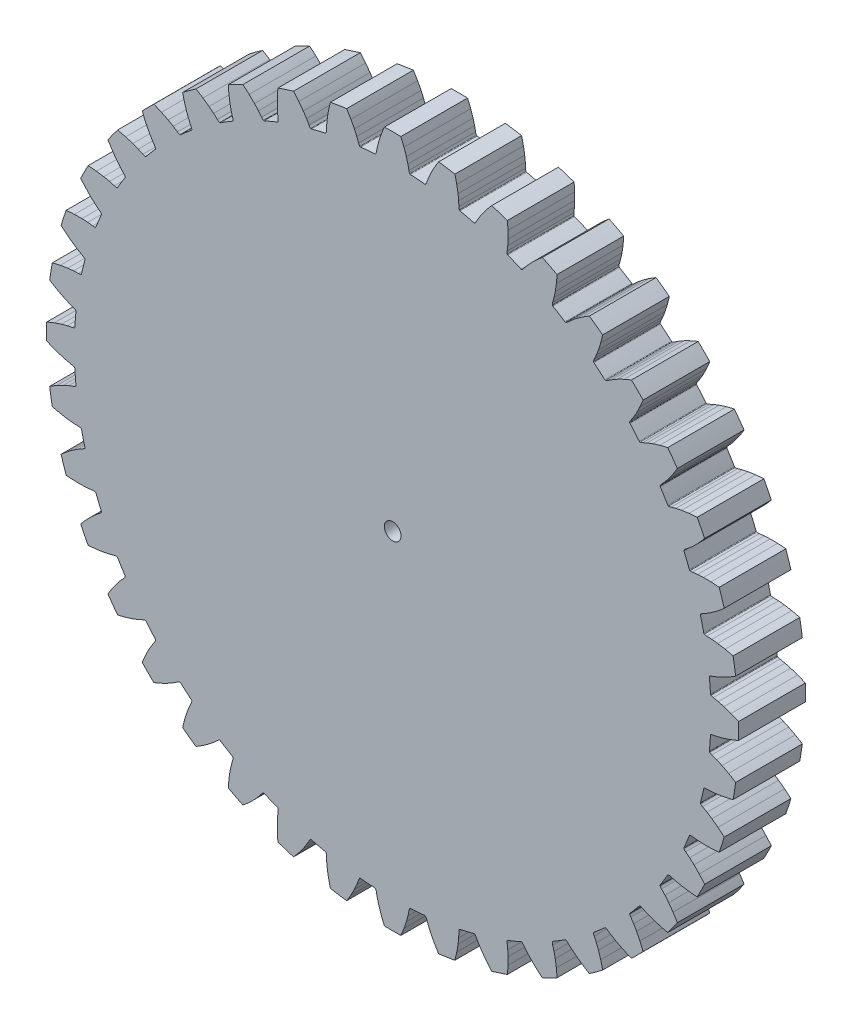
SolidWorks part; units mm, degrees
ref_plane "Front Plane" through (0, 0, 0) normal (0, 0, 1) x (1, 0, 0)
ref_plane "Top Plane" through (0, 0, 0) normal (0, 1, 0) x (1, 0, 0)
ref_plane "Right Plane" through (0, 0, 0) normal (1, 0, 0) x (0, 0, -1)
sketch "Model" plane through (0, 0, 0) normal (0, 0, 1) x (1, 0, 0)
  arc A1 (60.4326, -4.7561) -> (60.5251, -3.3796) centre (0, 0) ccw
  arc A2 (60.6099, -3.2458) -> (60.5251, -3.3796) centre (60.6875, -3.3887) ccw
  arc A3 (61.0557, -3.0916) -> (60.6099, -3.2458) centre (61.2975, -4.5122) ccw
  arc A4 (61.0557, -3.0916) -> (62.0044, -2.8977) centre (58.5908, 11.3846) ccw
  arc A5 (62.0044, -2.8977) -> (63.0847, -2.6067) centre (57.4472, 16.1693) ccw
  arc A6 (63.0847, -2.6067) -> (64.4306, -2.1546) centre (56.7644, 18.4435) ccw
  arc A7 (64.4306, -2.1546) -> (65.8858, -1.5642) centre (55.0531, 23.0418) ccw
  arc A8 (65.8858, -1.5642) -> (65.8858, 1.5642) centre (0, 0) ccw
  arc A9 (65.8858, 1.5642) -> (64.4306, 2.1546) centre (55.0531, -23.0418) ccw
  arc A10 (64.4306, 2.1546) -> (63.0847, 2.6067) centre (56.7644, -18.4435) ccw
  arc A11 (63.0847, 2.6067) -> (62.0044, 2.8977) centre (57.4472, -16.1693) ccw
  arc A12 (62.0044, 2.8977) -> (61.0557, 3.0916) centre (58.5908, -11.3846) ccw
  arc A13 (60.6099, 3.2458) -> (61.0557, 3.0916) centre (61.2975, 4.5122) ccw
  arc A14 (60.5251, 3.3796) -> (60.6099, 3.2458) centre (60.6875, 3.3887) ccw
  arc A15 (60.5251, 3.3796) -> (60.3087, 6.1302) centre (0, 0) ccw
  arc A16 (60.3715, 6.2757) -> (60.3087, 6.1302) centre (60.4705, 6.1466) ccw
  arc A17 (60.7876, 6.4977) -> (60.3715, 6.2757) centre (61.2487, 5.1324) ccw
  arc A18 (60.7876, 6.4977) -> (61.6943, 6.8376) centre (56.0885, 20.41) ccw
  arc A19 (61.6943, 6.8376) -> (62.7158, 7.294) centre (54.2105, 24.957) ccw
  arc A20 (62.7158, 7.294) -> (63.9745, 7.9511) centre (53.1804, 27.0964) ccw
  arc A21 (63.9745, 7.9511) -> (65.3193, 8.7619) centre (50.7708, 31.3703) ccw
  arc A22 (65.3193, 8.7619) -> (64.8299, 11.8517) centre (0, 0) ccw
  arc A23 (64.8299, 11.8517) -> (63.3003, 12.2073) centre (57.9798, -14.1459) ccw
  arc A24 (63.3003, 12.2073) -> (61.9002, 12.4432) centre (58.9508, -9.3365) ccw
  arc A25 (61.9002, 12.4432) -> (60.7877, 12.5616) centre (59.2694, -6.9835) ccw
  arc A26 (60.7877, 12.5616) -> (59.8203, 12.6047) centre (59.6504, -2.0788) ccw
  arc A27 (59.356, 12.6873) -> (59.8203, 12.6047) centre (59.837, 14.0457) ccw
  arc A28 (59.2513, 12.8063) -> (59.356, 12.6873) centre (59.4102, 12.8406) ccw
  arc A29 (59.2513, 12.8063) -> (58.6072, 15.4891) centre (0, 0) ccw
  arc A30 (58.6465, 15.6426) -> (58.6072, 15.4891) centre (58.7644, 15.5306) ccw
  arc A31 (59.0227, 15.9269) -> (58.6465, 15.6426) centre (59.6918, 14.6506) ccw
  arc A32 (59.0227, 15.9269) -> (59.8651, 16.4045) centre (52.2052, 28.9329) ccw
  arc A33 (59.8651, 16.4045) -> (60.8026, 17.0152) centre (49.639, 33.1301) ccw
  arc A34 (60.8026, 17.0152) -> (61.943, 17.861) centre (48.2868, 35.082) ccw
  arc A35 (61.943, 17.861) -> (63.1444, 18.8722) centre (45.2383, 38.9263) ccw
  arc A36 (63.1444, 18.8722) -> (62.1777, 21.8474) centre (0, 0) ccw
  arc A37 (62.1777, 21.8474) -> (60.6114, 21.9594) centre (59.4789, -4.9017) ccw
  arc A38 (60.6114, 21.9594) -> (59.1916, 21.9733) centre (59.6855, 0.0004) ccw
  arc A39 (59.1916, 21.9733) -> (58.0742, 21.9163) centre (59.6322, 2.3742) ccw
  arc A40 (58.0742, 21.9163) -> (57.112, 21.8075) centre (59.2412, 7.2782) ccw
  arc A41 (56.6405, 21.8164) -> (57.112, 21.8075) centre (56.9031, 23.2334) ccw
  arc A42 (56.5185, 21.9175) -> (56.6405, 21.8164) centre (56.6701, 21.9763) ccw
  arc A43 (56.5185, 21.9175) -> (55.4626, 24.4666) centre (0, 0) ccw
  arc A44 (55.4774, 24.6243) -> (55.4626, 24.4666) centre (55.6114, 24.5322) ccw
  arc A45 (55.8045, 24.9641) -> (55.4774, 24.6243) centre (56.665, 23.8081) ccw
  arc A46 (55.8045, 24.9641) -> (56.5618, 25.5675) centre (47.0363, 36.7434) ccw
  arc A47 (56.5618, 25.5675) -> (57.3922, 26.3173) centre (43.8451, 40.4875) ccw
  arc A48 (57.3922, 26.3173) -> (58.3863, 27.3311) centre (42.2043, 42.2038) ccw
  arc A49 (58.3863, 27.3311) -> (59.4147, 28.5178) centre (38.5919, 45.5239) ccw
  arc A50 (59.4147, 28.5178) -> (57.9945, 31.3052) centre (0, 0) ccw
  arc A51 (57.9945, 31.3052) -> (56.4299, 31.1707) centre (59.5134, 4.4632) ccw
  arc A52 (56.4299, 31.1707) -> (55.0254, 30.9624) centre (58.9507, 9.3372) ccw
  arc A53 (55.0254, 30.9624) -> (53.9308, 30.7312) centre (58.5266, 11.6735) ccw
  arc A54 (53.9308, 30.7312) -> (52.9974, 30.4733) centre (57.3733, 16.456) ccw
  arc A55 (52.5303, 30.4083) -> (52.9974, 30.4733) centre (52.568, 31.8489) ccw
  arc A56 (52.394, 30.4891) -> (52.5303, 30.4083) centre (52.5345, 30.5709) ccw
  arc A57 (52.394, 30.4891) -> (50.9524, 32.8416) centre (0, 0) ccw
  arc A58 (50.9423, 32.9997) -> (50.9524, 32.8416) centre (51.0891, 32.9297) ccw
  arc A59 (51.2123, 33.3865) -> (50.9423, 32.9997) centre (52.243, 32.3793) ccw
  arc A60 (51.2123, 33.3865) -> (51.8658, 34.101) centre (40.7093, 43.6491) ccw
  arc A61 (51.8658, 34.101) -> (52.5687, 34.9714) centre (36.9717, 46.8479) ccw
  arc A62 (52.5687, 34.9714) -> (53.392, 36.1282) centre (35.0826, 48.2864) ccw
  arc A63 (53.392, 36.1282) -> (54.2221, 37.4613) centre (30.9953, 51.0006) ccw
  arc A64 (54.2221, 37.4613) -> (52.3833, 39.9921) centre (0, 0) ccw
  arc A65 (52.3833, 39.9921) -> (50.859, 39.6145) centre (58.0825, 13.7182) ccw
  arc A66 (50.859, 39.6145) -> (49.5044, 39.1891) centre (56.7642, 18.4442) ccw
  arc A67 (49.5044, 39.1891) -> (48.4594, 38.7895) centre (55.9799, 20.6854) ccw
  arc A68 (48.4594, 38.7895) -> (47.5779, 38.3888) centre (54.0927, 25.2285) ccw
  arc A69 (47.1266, 38.2515) -> (47.5779, 38.3888) centre (46.9385, 39.6803) ccw
  arc A70 (46.9794, 38.31) -> (47.1266, 38.2515) centre (47.1054, 38.4128) ccw
  arc A71 (46.9794, 38.31) -> (45.1875, 40.408) centre (0, 0) ccw
  arc A72 (45.1528, 40.5626) -> (45.1875, 40.408) centre (45.3087, 40.5164) ccw
  arc A73 (45.359, 40.9868) -> (45.1528, 40.5626) centre (46.5345, 40.1533) ccw
  arc A74 (45.359, 40.9868) -> (45.8927, 41.7947) centre (33.3799, 49.4801) ccw
  arc A75 (45.8927, 41.7947) -> (46.4508, 42.7644) centre (29.1879, 52.0548) ccw
  arc A76 (46.4508, 42.7644) -> (47.0829, 44.0358) centre (27.097, 53.1801) ccw
  arc A77 (47.0829, 44.0358) -> (47.6943, 45.4822) centre (22.6354, 55.2214) ccw
  arc A78 (47.6943, 45.4822) -> (45.4822, 47.6943) centre (0, 0) ccw
  arc A79 (45.4822, 47.6943) -> (44.0358, 47.0829) centre (55.2214, 22.6354) ccw
  arc A80 (44.0358, 47.0829) -> (42.7644, 46.4508) centre (53.1801, 27.097) ccw
  arc A81 (42.7644, 46.4508) -> (41.7947, 45.8927) centre (52.0548, 29.1879) ccw
  arc A82 (41.7947, 45.8927) -> (40.9868, 45.359) centre (49.4801, 33.3799) ccw
  arc A83 (40.5626, 45.1528) -> (40.9868, 45.359) centre (40.1533, 46.5345) ccw
  arc A84 (40.408, 45.1875) -> (40.5626, 45.1528) centre (40.5164, 45.3087) ccw
  arc A85 (40.408, 45.1875) -> (38.31, 46.9794) centre (0, 0) ccw
  arc A86 (38.2515, 47.1266) -> (38.31, 46.9794) centre (38.4128, 47.1054) ccw
  arc A87 (38.3888, 47.5779) -> (38.2515, 47.1266) centre (39.6803, 46.9385) ccw
  arc A88 (38.3888, 47.5779) -> (38.7895, 48.4594) centre (25.2285, 54.0927) ccw
  arc A89 (38.7895, 48.4594) -> (39.1891, 49.5044) centre (20.6854, 55.9799) ccw
  arc A90 (39.1891, 49.5044) -> (39.6145, 50.859) centre (18.4442, 56.7642) ccw
  arc A91 (39.6145, 50.859) -> (39.9921, 52.3833) centre (13.7182, 58.0825) ccw
  arc A92 (39.9921, 52.3833) -> (37.4613, 54.2221) centre (0, 0) ccw
  arc A93 (37.4613, 54.2221) -> (36.1282, 53.392) centre (51.0006, 30.9953) ccw
  arc A94 (36.1282, 53.392) -> (34.9714, 52.5687) centre (48.2864, 35.0826) ccw
  arc A95 (34.9714, 52.5687) -> (34.101, 51.8658) centre (46.8479, 36.9717) ccw
  arc A96 (34.101, 51.8658) -> (33.3865, 51.2123) centre (43.6491, 40.7093) ccw
  arc A97 (32.9997, 50.9423) -> (33.3865, 51.2123) centre (32.3793, 52.243) ccw
  arc A98 (32.8416, 50.9524) -> (32.9997, 50.9423) centre (32.9297, 51.0891) ccw
  arc A99 (32.8416, 50.9524) -> (30.4891, 52.394) centre (0, 0) ccw
  arc A100 (30.4083, 52.5303) -> (30.4891, 52.394) centre (30.5709, 52.5345) ccw
  arc A101 (30.4733, 52.9974) -> (30.4083, 52.5303) centre (31.8489, 52.568) ccw
  arc A102 (30.4733, 52.9974) -> (30.7312, 53.9308) centre (16.456, 57.3733) ccw
  arc A103 (30.7312, 53.9308) -> (30.9624, 55.0254) centre (11.6735, 58.5266) ccw
  arc A104 (30.9624, 55.0254) -> (31.1707, 56.4299) centre (9.3372, 58.9507) ccw
  arc A105 (31.1707, 56.4299) -> (31.3052, 57.9945) centre (4.4632, 59.5134) ccw
  arc A106 (31.3052, 57.9945) -> (28.5178, 59.4147) centre (0, 0) ccw
  arc A107 (28.5178, 59.4147) -> (27.3311, 58.3863) centre (45.5239, 38.5919) ccw
  arc A108 (27.3311, 58.3863) -> (26.3173, 57.3922) centre (42.2038, 42.2043) ccw
  arc A109 (26.3173, 57.3922) -> (25.5675, 56.5618) centre (40.4875, 43.8451) ccw
  arc A110 (25.5675, 56.5618) -> (24.9641, 55.8045) centre (36.7434, 47.0363) ccw
  arc A111 (24.6243, 55.4774) -> (24.9641, 55.8045) centre (23.8081, 56.665) ccw
  arc A112 (24.4666, 55.4626) -> (24.6243, 55.4774) centre (24.5322, 55.6114) ccw
  arc A113 (24.4666, 55.4626) -> (21.9175, 56.5185) centre (0, 0) ccw
  arc A114 (21.8164, 56.6405) -> (21.9175, 56.5185) centre (21.9763, 56.6701) ccw
  arc A115 (21.8075, 57.112) -> (21.8164, 56.6405) centre (23.2334, 56.9031) ccw
  arc A116 (21.8075, 57.112) -> (21.9163, 58.0742) centre (7.2782, 59.2412) ccw
  arc A117 (21.9163, 58.0742) -> (21.9733, 59.1916) centre (2.3742, 59.6322) ccw
  arc A118 (21.9733, 59.1916) -> (21.9594, 60.6114) centre (0.0004, 59.6855) ccw
  arc A119 (21.9594, 60.6114) -> (21.8474, 62.1777) centre (-4.9017, 59.4789) ccw
  arc A120 (21.8474, 62.1777) -> (18.8722, 63.1444) centre (0, 0) ccw
  arc A121 (18.8722, 63.1444) -> (17.861, 61.943) centre (38.9263, 45.2383) ccw
  arc A122 (17.861, 61.943) -> (17.0152, 60.8026) centre (35.082, 48.2868) ccw
  arc A123 (17.0152, 60.8026) -> (16.4045, 59.8651) centre (33.1301, 49.639) ccw
  arc A124 (16.4045, 59.8651) -> (15.9269, 59.0227) centre (28.9329, 52.2052) ccw
  arc A125 (15.6426, 58.6465) -> (15.9269, 59.0227) centre (14.6506, 59.6918) ccw
  arc A126 (15.4891, 58.6072) -> (15.6426, 58.6465) centre (15.5306, 58.7644) ccw
  arc A127 (15.4891, 58.6072) -> (12.8063, 59.2513) centre (0, 0) ccw
  arc A128 (12.6873, 59.356) -> (12.8063, 59.2513) centre (12.8406, 59.4102) ccw
  arc A129 (12.6047, 59.8203) -> (12.6873, 59.356) centre (14.0457, 59.837) ccw
  arc A130 (12.6047, 59.8203) -> (12.5616, 60.7877) centre (-2.0788, 59.6504) ccw
  arc A131 (12.5616, 60.7877) -> (12.4432, 61.9002) centre (-6.9835, 59.2694) ccw
  arc A132 (12.4432, 61.9002) -> (12.2073, 63.3003) centre (-9.3365, 58.9508) ccw
  arc A133 (12.2073, 63.3003) -> (11.8517, 64.8299) centre (-14.1459, 57.9798) ccw
  arc A134 (11.8517, 64.8299) -> (8.7619, 65.3193) centre (0, 0) ccw
  arc A135 (8.7619, 65.3193) -> (7.9511, 63.9745) centre (31.3703, 50.7708) ccw
  arc A136 (7.9511, 63.9745) -> (7.294, 62.7158) centre (27.0964, 53.1804) ccw
  arc A137 (7.294, 62.7158) -> (6.8376, 61.6943) centre (24.957, 54.2105) ccw
  arc A138 (6.8376, 61.6943) -> (6.4977, 60.7876) centre (20.41, 56.0885) ccw
  arc A139 (6.2757, 60.3715) -> (6.4977, 60.7876) centre (5.1324, 61.2487) ccw
  arc A140 (6.1302, 60.3087) -> (6.2757, 60.3715) centre (6.1466, 60.4705) ccw
  arc A141 (6.1302, 60.3087) -> (3.3796, 60.5251) centre (0, 0) ccw
  arc A142 (3.2458, 60.6099) -> (3.3796, 60.5251) centre (3.3887, 60.6875) ccw
  arc A143 (3.0916, 61.0557) -> (3.2458, 60.6099) centre (4.5122, 61.2975) ccw
  arc A144 (3.0916, 61.0557) -> (2.8977, 62.0044) centre (-11.3846, 58.5908) ccw
  arc A145 (2.8977, 62.0044) -> (2.6067, 63.0847) centre (-16.1693, 57.4472) ccw
  arc A146 (2.6067, 63.0847) -> (2.1546, 64.4306) centre (-18.4435, 56.7644) ccw
  arc A147 (2.1546, 64.4306) -> (1.5642, 65.8858) centre (-23.0418, 55.0531) ccw
  arc A148 (1.5642, 65.8858) -> (-1.5642, 65.8858) centre (0, 0) ccw
  arc A149 (-1.5642, 65.8858) -> (-2.1546, 64.4306) centre (23.0418, 55.0531) ccw
  arc A150 (-2.1546, 64.4306) -> (-2.6067, 63.0847) centre (18.4435, 56.7644) ccw
  arc A151 (-2.6067, 63.0847) -> (-2.8977, 62.0044) centre (16.1693, 57.4472) ccw
  arc A152 (-2.8977, 62.0044) -> (-3.0916, 61.0557) centre (11.3846, 58.5908) ccw
  arc A153 (-3.2458, 60.6099) -> (-3.0916, 61.0557) centre (-4.5122, 61.2975) ccw
  arc A154 (-3.3796, 60.5251) -> (-3.2458, 60.6099) centre (-3.3887, 60.6875) ccw
  arc A155 (-3.3796, 60.5251) -> (-6.1302, 60.3087) centre (0, 0) ccw
  arc A156 (-6.2757, 60.3715) -> (-6.1302, 60.3087) centre (-6.1466, 60.4705) ccw
  arc A157 (-6.4977, 60.7876) -> (-6.2757, 60.3715) centre (-5.1324, 61.2487) ccw
  arc A158 (-6.4977, 60.7876) -> (-6.8376, 61.6943) centre (-20.41, 56.0885) ccw
  arc A159 (-6.8376, 61.6943) -> (-7.294, 62.7158) centre (-24.957, 54.2105) ccw
  arc A160 (-7.294, 62.7158) -> (-7.9511, 63.9745) centre (-27.0964, 53.1804) ccw
  arc A161 (-7.9511, 63.9745) -> (-8.7619, 65.3193) centre (-31.3703, 50.7708) ccw
  arc A162 (-8.7619, 65.3193) -> (-11.8517, 64.8299) centre (0, 0) ccw
  arc A163 (-11.8517, 64.8299) -> (-12.2073, 63.3003) centre (14.1459, 57.9798) ccw
  arc A164 (-12.2073, 63.3003) -> (-12.4432, 61.9002) centre (9.3365, 58.9508) ccw
  arc A165 (-12.4432, 61.9002) -> (-12.5616, 60.7877) centre (6.9835, 59.2694) ccw
  arc A166 (-12.5616, 60.7877) -> (-12.6047, 59.8203) centre (2.0788, 59.6504) ccw
  arc A167 (-12.6873, 59.356) -> (-12.6047, 59.8203) centre (-14.0457, 59.837) ccw
  arc A168 (-12.8063, 59.2513) -> (-12.6873, 59.356) centre (-12.8406, 59.4102) ccw
  arc A169 (-12.8063, 59.2513) -> (-15.4891, 58.6072) centre (0, 0) ccw
  arc A170 (-15.6426, 58.6465) -> (-15.4891, 58.6072) centre (-15.5306, 58.7644) ccw
  arc A171 (-15.9269, 59.0227) -> (-15.6426, 58.6465) centre (-14.6506, 59.6918) ccw
  arc A172 (-15.9269, 59.0227) -> (-16.4045, 59.8651) centre (-28.9329, 52.2052) ccw
  arc A173 (-16.4045, 59.8651) -> (-17.0152, 60.8026) centre (-33.1301, 49.639) ccw
  arc A174 (-17.0152, 60.8026) -> (-17.861, 61.943) centre (-35.082, 48.2868) ccw
  arc A175 (-17.861, 61.943) -> (-18.8722, 63.1444) centre (-38.9263, 45.2383) ccw
  arc A176 (-18.8722, 63.1444) -> (-21.8474, 62.1777) centre (0, 0) ccw
  arc A177 (-21.8474, 62.1777) -> (-21.9594, 60.6114) centre (4.9017, 59.4789) ccw
  arc A178 (-21.9594, 60.6114) -> (-21.9733, 59.1916) centre (-0.0004, 59.6855) ccw
  arc A179 (-21.9733, 59.1916) -> (-21.9163, 58.0742) centre (-2.3742, 59.6322) ccw
  arc A180 (-21.9163, 58.0742) -> (-21.8075, 57.112) centre (-7.2782, 59.2412) ccw
  arc A181 (-21.8164, 56.6405) -> (-21.8075, 57.112) centre (-23.2334, 56.9031) ccw
  arc A182 (-21.9175, 56.5185) -> (-21.8164, 56.6405) centre (-21.9763, 56.6701) ccw
  arc A183 (-21.9175, 56.5185) -> (-24.4666, 55.4626) centre (0, 0) ccw
  arc A184 (-24.6243, 55.4774) -> (-24.4666, 55.4626) centre (-24.5322, 55.6114) ccw
  arc A185 (-24.9641, 55.8045) -> (-24.6243, 55.4774) centre (-23.8081, 56.665) ccw
  arc A186 (-24.9641, 55.8045) -> (-25.5675, 56.5618) centre (-36.7434, 47.0363) ccw
  arc A187 (-25.5675, 56.5618) -> (-26.3173, 57.3922) centre (-40.4875, 43.8451) ccw
  arc A188 (-26.3173, 57.3922) -> (-27.3311, 58.3863) centre (-42.2038, 42.2043) ccw
  arc A189 (-27.3311, 58.3863) -> (-28.5178, 59.4147) centre (-45.5239, 38.5919) ccw
  arc A190 (-28.5178, 59.4147) -> (-31.3052, 57.9945) centre (0, 0) ccw
  arc A191 (-31.3052, 57.9945) -> (-31.1707, 56.4299) centre (-4.4632, 59.5134) ccw
  arc A192 (-31.1707, 56.4299) -> (-30.9624, 55.0254) centre (-9.3372, 58.9507) ccw
  arc A193 (-30.9624, 55.0254) -> (-30.7312, 53.9308) centre (-11.6735, 58.5266) ccw
  arc A194 (-30.7312, 53.9308) -> (-30.4733, 52.9974) centre (-16.456, 57.3733) ccw
  arc A195 (-30.4083, 52.5303) -> (-30.4733, 52.9974) centre (-31.8489, 52.568) ccw
  arc A196 (-30.4891, 52.394) -> (-30.4083, 52.5303) centre (-30.5709, 52.5345) ccw
  arc A197 (-30.4891, 52.394) -> (-32.8416, 50.9524) centre (0, 0) ccw
  arc A198 (-32.9997, 50.9423) -> (-32.8416, 50.9524) centre (-32.9297, 51.0891) ccw
  arc A199 (-33.3865, 51.2123) -> (-32.9997, 50.9423) centre (-32.3793, 52.243) ccw
  arc A200 (-33.3865, 51.2123) -> (-34.101, 51.8658) centre (-43.6491, 40.7093) ccw
  arc A201 (-34.101, 51.8658) -> (-34.9714, 52.5687) centre (-46.8479, 36.9717) ccw
  arc A202 (-34.9714, 52.5687) -> (-36.1282, 53.392) centre (-48.2864, 35.0826) ccw
  arc A203 (-36.1282, 53.392) -> (-37.4613, 54.2221) centre (-51.0006, 30.9953) ccw
  arc A204 (-37.4613, 54.2221) -> (-39.9921, 52.3833) centre (0, 0) ccw
  arc A205 (-39.9921, 52.3833) -> (-39.6145, 50.859) centre (-13.7182, 58.0825) ccw
  arc A206 (-39.6145, 50.859) -> (-39.1891, 49.5044) centre (-18.4442, 56.7642) ccw
  arc A207 (-39.1891, 49.5044) -> (-38.7895, 48.4594) centre (-20.6854, 55.9799) ccw
  arc A208 (-38.7895, 48.4594) -> (-38.3888, 47.5779) centre (-25.2285, 54.0927) ccw
  arc A209 (-38.2515, 47.1266) -> (-38.3888, 47.5779) centre (-39.6803, 46.9385) ccw
  arc A210 (-38.31, 46.9794) -> (-38.2515, 47.1266) centre (-38.4128, 47.1054) ccw
  arc A211 (-38.31, 46.9794) -> (-40.408, 45.1875) centre (0, 0) ccw
  arc A212 (-40.5626, 45.1528) -> (-40.408, 45.1875) centre (-40.5164, 45.3087) ccw
  arc A213 (-40.9868, 45.359) -> (-40.5626, 45.1528) centre (-40.1533, 46.5345) ccw
  arc A214 (-40.9868, 45.359) -> (-41.7947, 45.8927) centre (-49.4801, 33.3799) ccw
  arc A215 (-41.7947, 45.8927) -> (-42.7644, 46.4508) centre (-52.0548, 29.1879) ccw
  arc A216 (-42.7644, 46.4508) -> (-44.0358, 47.0829) centre (-53.1801, 27.097) ccw
  arc A217 (-44.0358, 47.0829) -> (-45.4822, 47.6943) centre (-55.2214, 22.6354) ccw
  arc A218 (-45.4822, 47.6943) -> (-47.6943, 45.4822) centre (0, 0) ccw
  arc A219 (-47.6943, 45.4822) -> (-47.0829, 44.0358) centre (-22.6354, 55.2214) ccw
  arc A220 (-47.0829, 44.0358) -> (-46.4508, 42.7644) centre (-27.097, 53.1801) ccw
  arc A221 (-46.4508, 42.7644) -> (-45.8927, 41.7947) centre (-29.1879, 52.0548) ccw
  arc A222 (-45.8927, 41.7947) -> (-45.359, 40.9868) centre (-33.3799, 49.4801) ccw
  arc A223 (-45.1528, 40.5626) -> (-45.359, 40.9868) centre (-46.5345, 40.1533) ccw
  arc A224 (-45.1875, 40.408) -> (-45.1528, 40.5626) centre (-45.3087, 40.5164) ccw
  arc A225 (-45.1875, 40.408) -> (-46.9794, 38.31) centre (0, 0) ccw
  arc A226 (-47.1266, 38.2515) -> (-46.9794, 38.31) centre (-47.1054, 38.4128) ccw
  arc A227 (-47.5779, 38.3888) -> (-47.1266, 38.2515) centre (-46.9385, 39.6803) ccw
  arc A228 (-47.5779, 38.3888) -> (-48.4594, 38.7895) centre (-54.0927, 25.2285) ccw
  arc A229 (-48.4594, 38.7895) -> (-49.5044, 39.1891) centre (-55.9799, 20.6854) ccw
  arc A230 (-49.5044, 39.1891) -> (-50.859, 39.6145) centre (-56.7642, 18.4442) ccw
  arc A231 (-50.859, 39.6145) -> (-52.3833, 39.9921) centre (-58.0825, 13.7182) ccw
  arc A232 (-52.3833, 39.9921) -> (-54.2221, 37.4613) centre (0, 0) ccw
  arc A233 (-54.2221, 37.4613) -> (-53.392, 36.1282) centre (-30.9953, 51.0006) ccw
  arc A234 (-53.392, 36.1282) -> (-52.5687, 34.9714) centre (-35.0826, 48.2864) ccw
  arc A235 (-52.5687, 34.9714) -> (-51.8658, 34.101) centre (-36.9717, 46.8479) ccw
  arc A236 (-51.8658, 34.101) -> (-51.2123, 33.3865) centre (-40.7093, 43.6491) ccw
  arc A237 (-50.9423, 32.9997) -> (-51.2123, 33.3865) centre (-52.243, 32.3793) ccw
  arc A238 (-50.9524, 32.8416) -> (-50.9423, 32.9997) centre (-51.0891, 32.9297) ccw
  arc A239 (-50.9524, 32.8416) -> (-52.394, 30.4891) centre (0, 0) ccw
  arc A240 (-52.5303, 30.4083) -> (-52.394, 30.4891) centre (-52.5345, 30.5709) ccw
  arc A241 (-52.9974, 30.4733) -> (-52.5303, 30.4083) centre (-52.568, 31.8489) ccw
  arc A242 (-52.9974, 30.4733) -> (-53.9308, 30.7312) centre (-57.3733, 16.456) ccw
  arc A243 (-53.9308, 30.7312) -> (-55.0254, 30.9624) centre (-58.5266, 11.6735) ccw
  arc A244 (-55.0254, 30.9624) -> (-56.4299, 31.1707) centre (-58.9507, 9.3372) ccw
  arc A245 (-56.4299, 31.1707) -> (-57.9945, 31.3052) centre (-59.5134, 4.4632) ccw
  arc A246 (-57.9945, 31.3052) -> (-59.4147, 28.5178) centre (0, 0) ccw
  arc A247 (-59.4147, 28.5178) -> (-58.3863, 27.3311) centre (-38.5919, 45.5239) ccw
  arc A248 (-58.3863, 27.3311) -> (-57.3922, 26.3173) centre (-42.2043, 42.2038) ccw
  arc A249 (-57.3922, 26.3173) -> (-56.5618, 25.5675) centre (-43.8451, 40.4875) ccw
  arc A250 (-56.5618, 25.5675) -> (-55.8045, 24.9641) centre (-47.0363, 36.7434) ccw
  arc A251 (-55.4774, 24.6243) -> (-55.8045, 24.9641) centre (-56.665, 23.8081) ccw
  arc A252 (-55.4626, 24.4666) -> (-55.4774, 24.6243) centre (-55.6114, 24.5322) ccw
  arc A253 (-55.4626, 24.4666) -> (-56.5185, 21.9175) centre (0, 0) ccw
  arc A254 (-56.6405, 21.8164) -> (-56.5185, 21.9175) centre (-56.6701, 21.9763) ccw
  arc A255 (-57.112, 21.8075) -> (-56.6405, 21.8164) centre (-56.9031, 23.2334) ccw
  arc A256 (-57.112, 21.8075) -> (-58.0742, 21.9163) centre (-59.2412, 7.2782) ccw
  arc A257 (-58.0742, 21.9163) -> (-59.1916, 21.9733) centre (-59.6322, 2.3742) ccw
  arc A258 (-59.1916, 21.9733) -> (-60.6114, 21.9594) centre (-59.6855, 0.0004) ccw
  arc A259 (-60.6114, 21.9594) -> (-62.1777, 21.8474) centre (-59.4789, -4.9017) ccw
  arc A260 (-62.1777, 21.8474) -> (-63.1444, 18.8722) centre (0, 0) ccw
  arc A261 (-63.1444, 18.8722) -> (-61.943, 17.861) centre (-45.2383, 38.9263) ccw
  arc A262 (-61.943, 17.861) -> (-60.8026, 17.0152) centre (-48.2868, 35.082) ccw
  arc A263 (-60.8026, 17.0152) -> (-59.8651, 16.4045) centre (-49.639, 33.1301) ccw
  arc A264 (-59.8651, 16.4045) -> (-59.0227, 15.9269) centre (-52.2052, 28.9329) ccw
  arc A265 (-58.6465, 15.6426) -> (-59.0227, 15.9269) centre (-59.6918, 14.6506) ccw
  arc A266 (-58.6072, 15.4891) -> (-58.6465, 15.6426) centre (-58.7644, 15.5306) ccw
  arc A267 (-58.6072, 15.4891) -> (-59.2513, 12.8063) centre (0, 0) ccw
  arc A268 (-59.356, 12.6873) -> (-59.2513, 12.8063) centre (-59.4102, 12.8406) ccw
  arc A269 (-59.8203, 12.6047) -> (-59.356, 12.6873) centre (-59.837, 14.0457) ccw
  arc A270 (-59.8203, 12.6047) -> (-60.7877, 12.5616) centre (-59.6504, -2.0788) ccw
  arc A271 (-60.7877, 12.5616) -> (-61.9002, 12.4432) centre (-59.2694, -6.9835) ccw
  arc A272 (-61.9002, 12.4432) -> (-63.3003, 12.2073) centre (-58.9508, -9.3365) ccw
  arc A273 (-63.3003, 12.2073) -> (-64.8299, 11.8517) centre (-57.9798, -14.1459) ccw
  arc A274 (-64.8299, 11.8517) -> (-65.3193, 8.7619) centre (0, 0) ccw
  arc A275 (-65.3193, 8.7619) -> (-63.9745, 7.9511) centre (-50.7708, 31.3703) ccw
  arc A276 (-63.9745, 7.9511) -> (-62.7158, 7.294) centre (-53.1804, 27.0964) ccw
  arc A277 (-62.7158, 7.294) -> (-61.6943, 6.8376) centre (-54.2105, 24.957) ccw
  arc A278 (-61.6943, 6.8376) -> (-60.7876, 6.4977) centre (-56.0885, 20.41) ccw
  arc A279 (-60.3715, 6.2757) -> (-60.7876, 6.4977) centre (-61.2487, 5.1324) ccw
  arc A280 (-60.3087, 6.1302) -> (-60.3715, 6.2757) centre (-60.4705, 6.1466) ccw
  arc A281 (-60.3087, 6.1302) -> (-60.5251, 3.3796) centre (0, 0) ccw
  arc A282 (-60.6099, 3.2458) -> (-60.5251, 3.3796) centre (-60.6875, 3.3887) ccw
  arc A283 (-61.0557, 3.0916) -> (-60.6099, 3.2458) centre (-61.2975, 4.5122) ccw
  arc A284 (-61.0557, 3.0916) -> (-62.0044, 2.8977) centre (-58.5908, -11.3846) ccw
  arc A285 (-62.0044, 2.8977) -> (-63.0847, 2.6067) centre (-57.4472, -16.1693) ccw
  arc A286 (-63.0847, 2.6067) -> (-64.4306, 2.1546) centre (-56.7644, -18.4435) ccw
  arc A287 (-64.4306, 2.1546) -> (-65.8858, 1.5642) centre (-55.0531, -23.0418) ccw
  arc A288 (-65.8858, 1.5642) -> (-65.8858, -1.5642) centre (0, 0) ccw
  arc A289 (-65.8858, -1.5642) -> (-64.4306, -2.1546) centre (-55.0531, 23.0418) ccw
  arc A290 (-64.4306, -2.1546) -> (-63.0847, -2.6067) centre (-56.7644, 18.4435) ccw
  arc A291 (-63.0847, -2.6067) -> (-62.0044, -2.8977) centre (-57.4472, 16.1693) ccw
  arc A292 (-62.0044, -2.8977) -> (-61.0557, -3.0916) centre (-58.5908, 11.3846) ccw
  arc A293 (-60.6099, -3.2458) -> (-61.0557, -3.0916) centre (-61.2975, -4.5122) ccw
  arc A294 (-60.5251, -3.3796) -> (-60.6099, -3.2458) centre (-60.6875, -3.3887) ccw
  arc A295 (-60.5251, -3.3796) -> (-60.3087, -6.1302) centre (0, 0) ccw
  arc A296 (-60.3715, -6.2757) -> (-60.3087, -6.1302) centre (-60.4705, -6.1466) ccw
  arc A297 (-60.7876, -6.4977) -> (-60.3715, -6.2757) centre (-61.2487, -5.1324) ccw
  arc A298 (-60.7876, -6.4977) -> (-61.6943, -6.8376) centre (-56.0885, -20.41) ccw
  arc A299 (-61.6943, -6.8376) -> (-62.7158, -7.294) centre (-54.2105, -24.957) ccw
  arc A300 (-62.7158, -7.294) -> (-63.9745, -7.9511) centre (-53.1804, -27.0964) ccw
  arc A301 (-63.9745, -7.9511) -> (-65.3193, -8.7619) centre (-50.7708, -31.3703) ccw
  arc A302 (-65.3193, -8.7619) -> (-64.8299, -11.8517) centre (0, 0) ccw
  arc A303 (-64.8299, -11.8517) -> (-63.3003, -12.2073) centre (-57.9798, 14.1459) ccw
  arc A304 (-63.3003, -12.2073) -> (-61.9002, -12.4432) centre (-58.9508, 9.3365) ccw
  arc A305 (-61.9002, -12.4432) -> (-60.7877, -12.5616) centre (-59.2694, 6.9835) ccw
  arc A306 (-60.7877, -12.5616) -> (-59.8203, -12.6047) centre (-59.6504, 2.0788) ccw
  arc A307 (-59.356, -12.6873) -> (-59.8203, -12.6047) centre (-59.837, -14.0457) ccw
  arc A308 (-59.2513, -12.8063) -> (-59.356, -12.6873) centre (-59.4102, -12.8406) ccw
  arc A309 (-59.2513, -12.8063) -> (-58.6072, -15.4891) centre (0, 0) ccw
  arc A310 (-58.6465, -15.6426) -> (-58.6072, -15.4891) centre (-58.7644, -15.5306) ccw
  arc A311 (-59.0227, -15.9269) -> (-58.6465, -15.6426) centre (-59.6918, -14.6506) ccw
  arc A312 (-59.0227, -15.9269) -> (-59.8651, -16.4045) centre (-52.2052, -28.9329) ccw
  arc A313 (-59.8651, -16.4045) -> (-60.8026, -17.0152) centre (-49.639, -33.1301) ccw
  arc A314 (-60.8026, -17.0152) -> (-61.943, -17.861) centre (-48.2868, -35.082) ccw
  arc A315 (-61.943, -17.861) -> (-63.1444, -18.8722) centre (-45.2383, -38.9263) ccw
  arc A316 (-63.1444, -18.8722) -> (-62.1777, -21.8474) centre (0, 0) ccw
  arc A317 (-62.1777, -21.8474) -> (-60.6114, -21.9594) centre (-59.4789, 4.9017) ccw
  arc A318 (-60.6114, -21.9594) -> (-59.1916, -21.9733) centre (-59.6855, -0.0004) ccw
  arc A319 (-59.1916, -21.9733) -> (-58.0742, -21.9163) centre (-59.6322, -2.3742) ccw
  arc A320 (-58.0742, -21.9163) -> (-57.112, -21.8075) centre (-59.2412, -7.2782) ccw
  arc A321 (-56.6405, -21.8164) -> (-57.112, -21.8075) centre (-56.9031, -23.2334) ccw
  arc A322 (-56.5185, -21.9175) -> (-56.6405, -21.8164) centre (-56.6701, -21.9763) ccw
  arc A323 (-56.5185, -21.9175) -> (-55.4626, -24.4666) centre (0, 0) ccw
  arc A324 (-55.4774, -24.6243) -> (-55.4626, -24.4666) centre (-55.6114, -24.5322) ccw
  arc A325 (-55.8045, -24.9641) -> (-55.4774, -24.6243) centre (-56.665, -23.8081) ccw
  arc A326 (-55.8045, -24.9641) -> (-56.5618, -25.5675) centre (-47.0363, -36.7434) ccw
  arc A327 (-56.5618, -25.5675) -> (-57.3922, -26.3173) centre (-43.8451, -40.4875) ccw
  arc A328 (-57.3922, -26.3173) -> (-58.3863, -27.3311) centre (-42.2043, -42.2038) ccw
  arc A329 (-58.3863, -27.3311) -> (-59.4147, -28.5178) centre (-38.5919, -45.5239) ccw
  arc A330 (-59.4147, -28.5178) -> (-57.9945, -31.3052) centre (0, 0) ccw
  arc A331 (-57.9945, -31.3052) -> (-56.4299, -31.1707) centre (-59.5134, -4.4632) ccw
  arc A332 (-56.4299, -31.1707) -> (-55.0254, -30.9624) centre (-58.9507, -9.3372) ccw
  arc A333 (-55.0254, -30.9624) -> (-53.9308, -30.7312) centre (-58.5266, -11.6735) ccw
  arc A334 (-53.9308, -30.7312) -> (-52.9974, -30.4733) centre (-57.3733, -16.456) ccw
  arc A335 (-52.5303, -30.4083) -> (-52.9974, -30.4733) centre (-52.568, -31.8489) ccw
  arc A336 (-52.394, -30.4891) -> (-52.5303, -30.4083) centre (-52.5345, -30.5709) ccw
  arc A337 (-52.394, -30.4891) -> (-50.9524, -32.8416) centre (0, 0) ccw
  arc A338 (-50.9423, -32.9997) -> (-50.9524, -32.8416) centre (-51.0891, -32.9297) ccw
  arc A339 (-51.2123, -33.3865) -> (-50.9423, -32.9997) centre (-52.243, -32.3793) ccw
  arc A340 (-51.2123, -33.3865) -> (-51.8658, -34.101) centre (-40.7093, -43.6491) ccw
  arc A341 (-51.8658, -34.101) -> (-52.5687, -34.9714) centre (-36.9717, -46.8479) ccw
  arc A342 (-52.5687, -34.9714) -> (-53.392, -36.1282) centre (-35.0826, -48.2864) ccw
  arc A343 (-53.392, -36.1282) -> (-54.2221, -37.4613) centre (-30.9953, -51.0006) ccw
  arc A344 (-54.2221, -37.4613) -> (-52.3833, -39.9921) centre (0, 0) ccw
  arc A345 (-52.3833, -39.9921) -> (-50.859, -39.6145) centre (-58.0825, -13.7182) ccw
  arc A346 (-50.859, -39.6145) -> (-49.5044, -39.1891) centre (-56.7642, -18.4442) ccw
  arc A347 (-49.5044, -39.1891) -> (-48.4594, -38.7895) centre (-55.9799, -20.6854) ccw
  arc A348 (-48.4594, -38.7895) -> (-47.5779, -38.3888) centre (-54.0927, -25.2285) ccw
  arc A349 (-47.1266, -38.2515) -> (-47.5779, -38.3888) centre (-46.9385, -39.6803) ccw
  arc A350 (-46.9794, -38.31) -> (-47.1266, -38.2515) centre (-47.1054, -38.4128) ccw
  arc A351 (-46.9794, -38.31) -> (-45.1875, -40.408) centre (0, 0) ccw
  arc A352 (-45.1528, -40.5626) -> (-45.1875, -40.408) centre (-45.3087, -40.5164) ccw
  arc A353 (-45.359, -40.9868) -> (-45.1528, -40.5626) centre (-46.5345, -40.1533) ccw
  arc A354 (-45.359, -40.9868) -> (-45.8927, -41.7947) centre (-33.3799, -49.4801) ccw
  arc A355 (-45.8927, -41.7947) -> (-46.4508, -42.7644) centre (-29.1879, -52.0548) ccw
  arc A356 (-46.4508, -42.7644) -> (-47.0829, -44.0358) centre (-27.097, -53.1801) ccw
  arc A357 (-47.0829, -44.0358) -> (-47.6943, -45.4822) centre (-22.6354, -55.2214) ccw
  arc A358 (-47.6943, -45.4822) -> (-45.4822, -47.6943) centre (0, 0) ccw
  arc A359 (-45.4822, -47.6943) -> (-44.0358, -47.0829) centre (-55.2214, -22.6354) ccw
  arc A360 (-44.0358, -47.0829) -> (-42.7644, -46.4508) centre (-53.1801, -27.097) ccw
  arc A361 (-42.7644, -46.4508) -> (-41.7947, -45.8927) centre (-52.0548, -29.1879) ccw
  arc A362 (-41.7947, -45.8927) -> (-40.9868, -45.359) centre (-49.4801, -33.3799) ccw
  arc A363 (-40.5626, -45.1528) -> (-40.9868, -45.359) centre (-40.1533, -46.5345) ccw
  arc A364 (-40.408, -45.1875) -> (-40.5626, -45.1528) centre (-40.5164, -45.3087) ccw
  arc A365 (-40.408, -45.1875) -> (-38.31, -46.9794) centre (0, 0) ccw
  arc A366 (-38.2515, -47.1266) -> (-38.31, -46.9794) centre (-38.4128, -47.1054) ccw
  arc A367 (-38.3888, -47.5779) -> (-38.2515, -47.1266) centre (-39.6803, -46.9385) ccw
  arc A368 (-38.3888, -47.5779) -> (-38.7895, -48.4594) centre (-25.2285, -54.0927) ccw
  arc A369 (-38.7895, -48.4594) -> (-39.1891, -49.5044) centre (-20.6854, -55.9799) ccw
  arc A370 (-39.1891, -49.5044) -> (-39.6145, -50.859) centre (-18.4442, -56.7642) ccw
  arc A371 (-39.6145, -50.859) -> (-39.9921, -52.3833) centre (-13.7182, -58.0825) ccw
  arc A372 (-39.9921, -52.3833) -> (-37.4613, -54.2221) centre (0, 0) ccw
  arc A373 (-37.4613, -54.2221) -> (-36.1282, -53.392) centre (-51.0006, -30.9953) ccw
  arc A374 (-36.1282, -53.392) -> (-34.9714, -52.5687) centre (-48.2864, -35.0826) ccw
  arc A375 (-34.9714, -52.5687) -> (-34.101, -51.8658) centre (-46.8479, -36.9717) ccw
  arc A376 (-34.101, -51.8658) -> (-33.3865, -51.2123) centre (-43.6491, -40.7093) ccw
  arc A377 (-32.9997, -50.9423) -> (-33.3865, -51.2123) centre (-32.3793, -52.243) ccw
  arc A378 (-32.8416, -50.9524) -> (-32.9997, -50.9423) centre (-32.9297, -51.0891) ccw
  arc A379 (-32.8416, -50.9524) -> (-30.4891, -52.394) centre (0, 0) ccw
  arc A380 (-30.4083, -52.5303) -> (-30.4891, -52.394) centre (-30.5709, -52.5345) ccw
  arc A381 (-30.4733, -52.9974) -> (-30.4083, -52.5303) centre (-31.8489, -52.568) ccw
  arc A382 (-30.4733, -52.9974) -> (-30.7312, -53.9308) centre (-16.456, -57.3733) ccw
  arc A383 (-30.7312, -53.9308) -> (-30.9624, -55.0254) centre (-11.6735, -58.5266) ccw
  arc A384 (-30.9624, -55.0254) -> (-31.1707, -56.4299) centre (-9.3372, -58.9507) ccw
  arc A385 (-31.1707, -56.4299) -> (-31.3052, -57.9945) centre (-4.4632, -59.5134) ccw
  arc A386 (-31.3052, -57.9945) -> (-28.5178, -59.4147) centre (0, 0) ccw
  arc A387 (-28.5178, -59.4147) -> (-27.3311, -58.3863) centre (-45.5239, -38.5919) ccw
  arc A388 (-27.3311, -58.3863) -> (-26.3173, -57.3922) centre (-42.2038, -42.2043) ccw
  arc A389 (-26.3173, -57.3922) -> (-25.5675, -56.5618) centre (-40.4875, -43.8451) ccw
  arc A390 (-25.5675, -56.5618) -> (-24.9641, -55.8045) centre (-36.7434, -47.0363) ccw
  arc A391 (-24.6243, -55.4774) -> (-24.9641, -55.8045) centre (-23.8081, -56.665) ccw
  arc A392 (-24.4666, -55.4626) -> (-24.6243, -55.4774) centre (-24.5322, -55.6114) ccw
  arc A393 (-24.4666, -55.4626) -> (-21.9175, -56.5185) centre (0, 0) ccw
  arc A394 (-21.8164, -56.6405) -> (-21.9175, -56.5185) centre (-21.9763, -56.6701) ccw
  arc A395 (-21.8075, -57.112) -> (-21.8164, -56.6405) centre (-23.2334, -56.9031) ccw
  arc A396 (-21.8075, -57.112) -> (-21.9163, -58.0742) centre (-7.2782, -59.2412) ccw
  arc A397 (-21.9163, -58.0742) -> (-21.9733, -59.1916) centre (-2.3742, -59.6322) ccw
  arc A398 (-21.9733, -59.1916) -> (-21.9594, -60.6114) centre (-0.0004, -59.6855) ccw
  arc A399 (-21.9594, -60.6114) -> (-21.8474, -62.1777) centre (4.9017, -59.4789) ccw
  arc A400 (-21.8474, -62.1777) -> (-18.8722, -63.1444) centre (0, 0) ccw
  arc A401 (-18.8722, -63.1444) -> (-17.861, -61.943) centre (-38.9263, -45.2383) ccw
  arc A402 (-17.861, -61.943) -> (-17.0152, -60.8026) centre (-35.082, -48.2868) ccw
  arc A403 (-17.0152, -60.8026) -> (-16.4045, -59.8651) centre (-33.1301, -49.639) ccw
  arc A404 (-16.4045, -59.8651) -> (-15.9269, -59.0227) centre (-28.9329, -52.2052) ccw
  arc A405 (-15.6426, -58.6465) -> (-15.9269, -59.0227) centre (-14.6506, -59.6918) ccw
  arc A406 (-15.4891, -58.6072) -> (-15.6426, -58.6465) centre (-15.5306, -58.7644) ccw
  arc A407 (-15.4891, -58.6072) -> (-12.8063, -59.2513) centre (0, 0) ccw
  arc A408 (-12.6873, -59.356) -> (-12.8063, -59.2513) centre (-12.8406, -59.4102) ccw
  arc A409 (-12.6047, -59.8203) -> (-12.6873, -59.356) centre (-14.0457, -59.837) ccw
  arc A410 (-12.6047, -59.8203) -> (-12.5616, -60.7877) centre (2.0788, -59.6504) ccw
  arc A411 (-12.5616, -60.7877) -> (-12.4432, -61.9002) centre (6.9835, -59.2694) ccw
  arc A412 (-12.4432, -61.9002) -> (-12.2073, -63.3003) centre (9.3365, -58.9508) ccw
  arc A413 (-12.2073, -63.3003) -> (-11.8517, -64.8299) centre (14.1459, -57.9798) ccw
  arc A414 (-11.8517, -64.8299) -> (-8.7619, -65.3193) centre (0, 0) ccw
  arc A415 (-8.7619, -65.3193) -> (-7.9511, -63.9745) centre (-31.3703, -50.7708) ccw
  arc A416 (-7.9511, -63.9745) -> (-7.294, -62.7158) centre (-27.0964, -53.1804) ccw
  arc A417 (-7.294, -62.7158) -> (-6.8376, -61.6943) centre (-24.957, -54.2105) ccw
  arc A418 (-6.8376, -61.6943) -> (-6.4977, -60.7876) centre (-20.41, -56.0885) ccw
  arc A419 (-6.2757, -60.3715) -> (-6.4977, -60.7876) centre (-5.1324, -61.2487) ccw
  arc A420 (-6.1302, -60.3087) -> (-6.2757, -60.3715) centre (-6.1466, -60.4705) ccw
  arc A421 (-6.1302, -60.3087) -> (-3.3796, -60.5251) centre (0, 0) ccw
  arc A422 (-3.2458, -60.6099) -> (-3.3796, -60.5251) centre (-3.3887, -60.6875) ccw
  arc A423 (-3.0916, -61.0557) -> (-3.2458, -60.6099) centre (-4.5122, -61.2975) ccw
  arc A424 (-3.0916, -61.0557) -> (-2.8977, -62.0044) centre (11.3846, -58.5908) ccw
  arc A425 (-2.8977, -62.0044) -> (-2.6067, -63.0847) centre (16.1693, -57.4472) ccw
  arc A426 (-2.6067, -63.0847) -> (-2.1546, -64.4306) centre (18.4435, -56.7644) ccw
  arc A427 (-2.1546, -64.4306) -> (-1.5642, -65.8858) centre (23.0418, -55.0531) ccw
  arc A428 (-1.5642, -65.8858) -> (1.5642, -65.8858) centre (0, 0) ccw
  arc A429 (1.5642, -65.8858) -> (2.1546, -64.4306) centre (-23.0418, -55.0531) ccw
  arc A430 (2.1546, -64.4306) -> (2.6067, -63.0847) centre (-18.4435, -56.7644) ccw
  arc A431 (2.6067, -63.0847) -> (2.8977, -62.0044) centre (-16.1693, -57.4472) ccw
  arc A432 (2.8977, -62.0044) -> (3.0916, -61.0557) centre (-11.3846, -58.5908) ccw
  arc A433 (3.2458, -60.6099) -> (3.0916, -61.0557) centre (4.5122, -61.2975) ccw
  arc A434 (3.3796, -60.5251) -> (3.2458, -60.6099) centre (3.3887, -60.6875) ccw
  arc A435 (3.3796, -60.5251) -> (6.1302, -60.3087) centre (0, 0) ccw
  arc A436 (6.2757, -60.3715) -> (6.1302, -60.3087) centre (6.1466, -60.4705) ccw
  arc A437 (6.4977, -60.7876) -> (6.2757, -60.3715) centre (5.1324, -61.2487) ccw
  arc A438 (6.4977, -60.7876) -> (6.8376, -61.6943) centre (20.41, -56.0885) ccw
  arc A439 (6.8376, -61.6943) -> (7.294, -62.7158) centre (24.957, -54.2105) ccw
  arc A440 (7.294, -62.7158) -> (7.9511, -63.9745) centre (27.0964, -53.1804) ccw
  arc A441 (7.9511, -63.9745) -> (8.7619, -65.3193) centre (31.3703, -50.7708) ccw
  arc A442 (8.7619, -65.3193) -> (11.8517, -64.8299) centre (0, 0) ccw
  arc A443 (11.8517, -64.8299) -> (12.2073, -63.3003) centre (-14.1459, -57.9798) ccw
  arc A444 (12.2073, -63.3003) -> (12.4432, -61.9002) centre (-9.3365, -58.9508) ccw
  arc A445 (12.4432, -61.9002) -> (12.5616, -60.7877) centre (-6.9835, -59.2694) ccw
  arc A446 (12.5616, -60.7877) -> (12.6047, -59.8203) centre (-2.0788, -59.6504) ccw
  arc A447 (12.6873, -59.356) -> (12.6047, -59.8203) centre (14.0457, -59.837) ccw
  arc A448 (12.8063, -59.2513) -> (12.6873, -59.356) centre (12.8406, -59.4102) ccw
  arc A449 (12.8063, -59.2513) -> (15.4891, -58.6072) centre (0, 0) ccw
  arc A450 (15.6426, -58.6465) -> (15.4891, -58.6072) centre (15.5306, -58.7644) ccw
  arc A451 (15.9269, -59.0227) -> (15.6426, -58.6465) centre (14.6506, -59.6918) ccw
  arc A452 (15.9269, -59.0227) -> (16.4045, -59.8651) centre (28.9329, -52.2052) ccw
  arc A453 (16.4045, -59.8651) -> (17.0152, -60.8026) centre (33.1301, -49.639) ccw
  arc A454 (17.0152, -60.8026) -> (17.861, -61.943) centre (35.082, -48.2868) ccw
  arc A455 (17.861, -61.943) -> (18.8722, -63.1444) centre (38.9263, -45.2383) ccw
  arc A456 (18.8722, -63.1444) -> (21.8474, -62.1777) centre (0, 0) ccw
  arc A457 (21.8474, -62.1777) -> (21.9594, -60.6114) centre (-4.9017, -59.4789) ccw
  arc A458 (21.9594, -60.6114) -> (21.9733, -59.1916) centre (0.0004, -59.6855) ccw
  arc A459 (21.9733, -59.1916) -> (21.9163, -58.0742) centre (2.3742, -59.6322) ccw
  arc A460 (21.9163, -58.0742) -> (21.8075, -57.112) centre (7.2782, -59.2412) ccw
  arc A461 (21.8164, -56.6405) -> (21.8075, -57.112) centre (23.2334, -56.9031) ccw
  arc A462 (21.9175, -56.5185) -> (21.8164, -56.6405) centre (21.9763, -56.6701) ccw
  arc A463 (21.9175, -56.5185) -> (24.4666, -55.4626) centre (0, 0) ccw
  arc A464 (24.6243, -55.4774) -> (24.4666, -55.4626) centre (24.5322, -55.6114) ccw
  arc A465 (24.9641, -55.8045) -> (24.6243, -55.4774) centre (23.8081, -56.665) ccw
  arc A466 (24.9641, -55.8045) -> (25.5675, -56.5618) centre (36.7434, -47.0363) ccw
  arc A467 (25.5675, -56.5618) -> (26.3173, -57.3922) centre (40.4875, -43.8451) ccw
  arc A468 (26.3173, -57.3922) -> (27.3311, -58.3863) centre (42.2038, -42.2043) ccw
  arc A469 (27.3311, -58.3863) -> (28.5178, -59.4147) centre (45.5239, -38.5919) ccw
  arc A470 (28.5178, -59.4147) -> (31.3052, -57.9945) centre (0, 0) ccw
  arc A471 (31.3052, -57.9945) -> (31.1707, -56.4299) centre (4.4632, -59.5134) ccw
  arc A472 (31.1707, -56.4299) -> (30.9624, -55.0254) centre (9.3372, -58.9507) ccw
  arc A473 (30.9624, -55.0254) -> (30.7312, -53.9308) centre (11.6735, -58.5266) ccw
  arc A474 (30.7312, -53.9308) -> (30.4733, -52.9974) centre (16.456, -57.3733) ccw
  arc A475 (30.4083, -52.5303) -> (30.4733, -52.9974) centre (31.8489, -52.568) ccw
  arc A476 (30.4891, -52.394) -> (30.4083, -52.5303) centre (30.5709, -52.5345) ccw
  arc A477 (30.4891, -52.394) -> (32.8416, -50.9524) centre (0, 0) ccw
  arc A478 (32.9997, -50.9423) -> (32.8416, -50.9524) centre (32.9297, -51.0891) ccw
  arc A479 (33.3865, -51.2123) -> (32.9997, -50.9423) centre (32.3793, -52.243) ccw
  arc A480 (33.3865, -51.2123) -> (34.101, -51.8658) centre (43.6491, -40.7093) ccw
  arc A481 (34.101, -51.8658) -> (34.9714, -52.5687) centre (46.8479, -36.9717) ccw
  arc A482 (34.9714, -52.5687) -> (36.1282, -53.392) centre (48.2864, -35.0826) ccw
  arc A483 (36.1282, -53.392) -> (37.4613, -54.2221) centre (51.0006, -30.9953) ccw
  arc A484 (37.4613, -54.2221) -> (39.9921, -52.3833) centre (0, 0) ccw
  arc A485 (39.9921, -52.3833) -> (39.6145, -50.859) centre (13.7182, -58.0825) ccw
  arc A486 (39.6145, -50.859) -> (39.1891, -49.5044) centre (18.4442, -56.7642) ccw
  arc A487 (39.1891, -49.5044) -> (38.7895, -48.4594) centre (20.6854, -55.9799) ccw
  arc A488 (38.7895, -48.4594) -> (38.3888, -47.5779) centre (25.2285, -54.0927) ccw
  arc A489 (38.2515, -47.1266) -> (38.3888, -47.5779) centre (39.6803, -46.9385) ccw
  arc A490 (38.31, -46.9794) -> (38.2515, -47.1266) centre (38.4128, -47.1054) ccw
  arc A491 (38.31, -46.9794) -> (40.408, -45.1875) centre (0, 0) ccw
  arc A492 (40.5626, -45.1528) -> (40.408, -45.1875) centre (40.5164, -45.3087) ccw
  arc A493 (40.9868, -45.359) -> (40.5626, -45.1528) centre (40.1533, -46.5345) ccw
  arc A494 (40.9868, -45.359) -> (41.7947, -45.8927) centre (49.4801, -33.3799) ccw
  arc A495 (41.7947, -45.8927) -> (42.7644, -46.4508) centre (52.0548, -29.1879) ccw
  arc A496 (42.7644, -46.4508) -> (44.0358, -47.0829) centre (53.1801, -27.097) ccw
  arc A497 (44.0358, -47.0829) -> (45.4822, -47.6943) centre (55.2214, -22.6354) ccw
  arc A498 (45.4822, -47.6943) -> (47.6943, -45.4822) centre (0, 0) ccw
  arc A499 (47.6943, -45.4822) -> (47.0829, -44.0358) centre (22.6354, -55.2214) ccw
  arc A500 (47.0829, -44.0358) -> (46.4508, -42.7644) centre (27.097, -53.1801) ccw
  arc A501 (46.4508, -42.7644) -> (45.8927, -41.7947) centre (29.1879, -52.0548) ccw
  arc A502 (45.8927, -41.7947) -> (45.359, -40.9868) centre (33.3799, -49.4801) ccw
  arc A503 (45.1528, -40.5626) -> (45.359, -40.9868) centre (46.5345, -40.1533) ccw
  arc A504 (45.1875, -40.408) -> (45.1528, -40.5626) centre (45.3087, -40.5164) ccw
  arc A505 (45.1875, -40.408) -> (46.9794, -38.31) centre (0, 0) ccw
  arc A506 (47.1266, -38.2515) -> (46.9794, -38.31) centre (47.1054, -38.4128) ccw
  arc A507 (47.5779, -38.3888) -> (47.1266, -38.2515) centre (46.9385, -39.6803) ccw
  arc A508 (47.5779, -38.3888) -> (48.4594, -38.7895) centre (54.0927, -25.2285) ccw
  arc A509 (48.4594, -38.7895) -> (49.5044, -39.1891) centre (55.9799, -20.6854) ccw
  arc A510 (49.5044, -39.1891) -> (50.859, -39.6145) centre (56.7642, -18.4442) ccw
  arc A511 (50.859, -39.6145) -> (52.3833, -39.9921) centre (58.0825, -13.7182) ccw
  arc A512 (52.3833, -39.9921) -> (54.2221, -37.4613) centre (0, 0) ccw
  arc A513 (54.2221, -37.4613) -> (53.392, -36.1282) centre (30.9953, -51.0006) ccw
  arc A514 (53.392, -36.1282) -> (52.5687, -34.9714) centre (35.0826, -48.2864) ccw
  arc A515 (52.5687, -34.9714) -> (51.8658, -34.101) centre (36.9717, -46.8479) ccw
  arc A516 (51.8658, -34.101) -> (51.2123, -33.3865) centre (40.7093, -43.6491) ccw
  arc A517 (50.9423, -32.9997) -> (51.2123, -33.3865) centre (52.243, -32.3793) ccw
  arc A518 (50.9524, -32.8416) -> (50.9423, -32.9997) centre (51.0891, -32.9297) ccw
  arc A519 (50.9524, -32.8416) -> (52.394, -30.4891) centre (0, 0) ccw
  arc A520 (52.5303, -30.4083) -> (52.394, -30.4891) centre (52.5345, -30.5709) ccw
  arc A521 (52.9974, -30.4733) -> (52.5303, -30.4083) centre (52.568, -31.8489) ccw
  arc A522 (52.9974, -30.4733) -> (53.9308, -30.7312) centre (57.3733, -16.456) ccw
  arc A523 (53.9308, -30.7312) -> (55.0254, -30.9624) centre (58.5266, -11.6735) ccw
  arc A524 (55.0254, -30.9624) -> (56.4299, -31.1707) centre (58.9507, -9.3372) ccw
  arc A525 (56.4299, -31.1707) -> (57.9945, -31.3052) centre (59.5134, -4.4632) ccw
  arc A526 (57.9945, -31.3052) -> (59.4147, -28.5178) centre (0, 0) ccw
  arc A527 (59.4147, -28.5178) -> (58.3863, -27.3311) centre (38.5919, -45.5239) ccw
  arc A528 (58.3863, -27.3311) -> (57.3922, -26.3173) centre (42.2043, -42.2038) ccw
  arc A529 (57.3922, -26.3173) -> (56.5618, -25.5675) centre (43.8451, -40.4875) ccw
  arc A530 (56.5618, -25.5675) -> (55.8045, -24.9641) centre (47.0363, -36.7434) ccw
  arc A531 (55.4774, -24.6243) -> (55.8045, -24.9641) centre (56.665, -23.8081) ccw
  arc A532 (55.4626, -24.4666) -> (55.4774, -24.6243) centre (55.6114, -24.5322) ccw
  arc A533 (55.4626, -24.4666) -> (56.5185, -21.9175) centre (0, 0) ccw
  arc A534 (56.6405, -21.8164) -> (56.5185, -21.9175) centre (56.6701, -21.9763) ccw
  arc A535 (57.112, -21.8075) -> (56.6405, -21.8164) centre (56.9031, -23.2334) ccw
  arc A536 (57.112, -21.8075) -> (58.0742, -21.9163) centre (59.2412, -7.2782) ccw
  arc A537 (58.0742, -21.9163) -> (59.1916, -21.9733) centre (59.6322, -2.3742) ccw
  arc A538 (59.1916, -21.9733) -> (60.6114, -21.9594) centre (59.6855, -0.0004) ccw
  arc A539 (60.6114, -21.9594) -> (62.1777, -21.8474) centre (59.4789, 4.9017) ccw
  arc A540 (62.1777, -21.8474) -> (63.1444, -18.8722) centre (0, 0) ccw
  arc A541 (63.1444, -18.8722) -> (61.943, -17.861) centre (45.2383, -38.9263) ccw
  arc A542 (61.943, -17.861) -> (60.8026, -17.0152) centre (48.2868, -35.082) ccw
  arc A543 (60.8026, -17.0152) -> (59.8651, -16.4045) centre (49.639, -33.1301) ccw
  arc A544 (59.8651, -16.4045) -> (59.0227, -15.9269) centre (52.2052, -28.9329) ccw
  arc A545 (58.6465, -15.6426) -> (59.0227, -15.9269) centre (59.6918, -14.6506) ccw
  arc A546 (58.6072, -15.4891) -> (58.6465, -15.6426) centre (58.7644, -15.5306) ccw
  arc A547 (58.6072, -15.4891) -> (59.2513, -12.8063) centre (0, 0) ccw
  arc A548 (59.356, -12.6873) -> (59.2513, -12.8063) centre (59.4102, -12.8406) ccw
  arc A549 (59.8203, -12.6047) -> (59.356, -12.6873) centre (59.837, -14.0457) ccw
  arc A550 (59.8203, -12.6047) -> (60.7877, -12.5616) centre (59.6504, 2.0788) ccw
  arc A551 (60.7877, -12.5616) -> (61.9002, -12.4432) centre (59.2694, 6.9835) ccw
  arc A552 (61.9002, -12.4432) -> (63.3003, -12.2073) centre (58.9508, 9.3365) ccw
  arc A553 (63.3003, -12.2073) -> (64.8299, -11.8517) centre (57.9798, 14.1459) ccw
  arc A554 (64.8299, -11.8517) -> (65.3193, -8.7619) centre (0, 0) ccw
  arc A555 (65.3193, -8.7619) -> (63.9745, -7.9511) centre (50.7708, -31.3703) ccw
  arc A556 (63.9745, -7.9511) -> (62.7158, -7.294) centre (53.1804, -27.0964) ccw
  arc A557 (62.7158, -7.294) -> (61.6943, -6.8376) centre (54.2105, -24.957) ccw
  arc A558 (61.6943, -6.8376) -> (60.7876, -6.4977) centre (56.0885, -20.41) ccw
  arc A559 (60.3715, -6.2757) -> (60.7876, -6.4977) centre (61.2487, -5.1324) ccw
  arc A560 (60.3087, -6.1302) -> (60.3715, -6.2757) centre (60.4705, -6.1466) ccw
  arc A561 (60.3087, -6.1302) -> (60.4326, -4.7561) centre (0, 0) ccw
extrude "Boss-Extrude1" add sketch "Model" along normal blind 12.7
sketch "Sketch2" plane through (0, 0, 12.7) normal (0, 0, 1) x (1, 0, 0)
  circle A0 centre (0, 0) radius 1.5875
  dimension "D1" = 3.175
extrude "Cut-Extrude1" cut sketch "Sketch2" against normal through all
